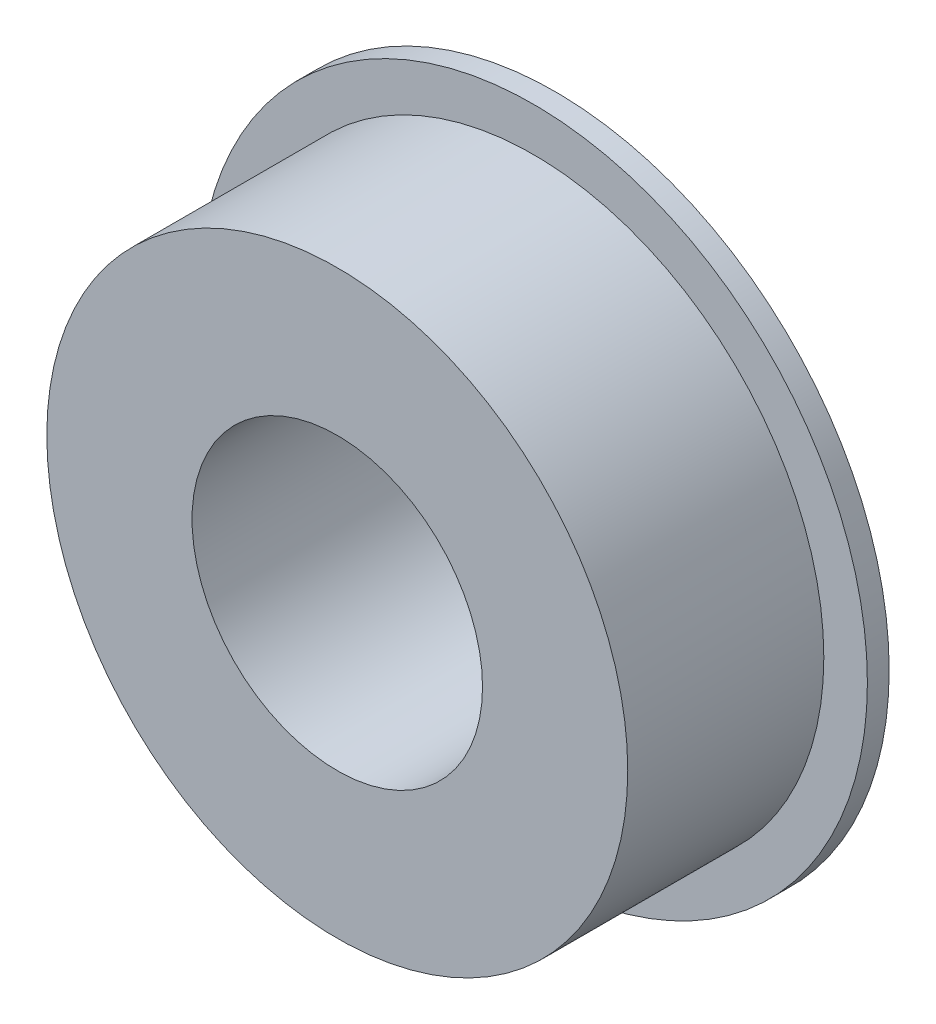
SolidWorks part; units mm, degrees
ref_plane "Front Plane" through (0, 0, 0) normal (0, 0, 1) x (1, 0, 0)
ref_plane "Top Plane" through (0, 0, 0) normal (0, 1, 0) x (1, 0, 0)
ref_plane "Right Plane" through (0, 0, 0) normal (1, 0, 0) x (0, 0, -1)
ref_axis "Axis1" through (0, 0, 55) along (0, 0, -1)
sketch "Sketch1" plane through (0, 0, 0) normal (1, 0, 0) x (0, 0, -1)
  line L0 (0, 0) -> (0, 4.6)
  line L1 (0, 4.6) -> (-0.3, 4.6)
  line L2 (0, 0) -> (-3, 0)
  line L3 (-55, 0) -> (55, 0) construction
  line L4 (-3, 0) -> (-3, 4)
  line L5 (-3, 4) -> (-0.3, 4)
  line L6 (-0.3, 4) -> (-0.3, 4.6)
revolve "Revolve1" add sketch "Sketch1" angle 360 about axis through (0, 0, 55) along (0, 0, -1)
hole_wizard "Ø4.0 (4) Diameter Hole1" positions "Sketch3" profile "Sketch2" hole size "Ø4.0" standard "ANSI Metric"
sketch "Sketch3" plane through (0, 0, 3) normal (0, 0, 1) x (1, 0, 0)
  point P0 (0, 0)
sketch "Sketch2" plane through (0, 0, 3) normal (1, 0, 0) x (0, -1, 0)
  line L0 (0, 0) -> (0, 57.4017)
  line L1 (0, 57.4017) -> (2, 56.2)
  line L2 (2, 56.2) -> (2, 0)
  line L5 (2, 0) -> (0, 0)
  line L10 (0, 57.4017) -> (-2, 56.2) construction
  line L11 (0, -6.35) -> (0, 107.95) construction
  dimension "Hole Dia." = 4
  dimension "Hole Depth" = 56.2
  dimension "Drill Angle" = 118
